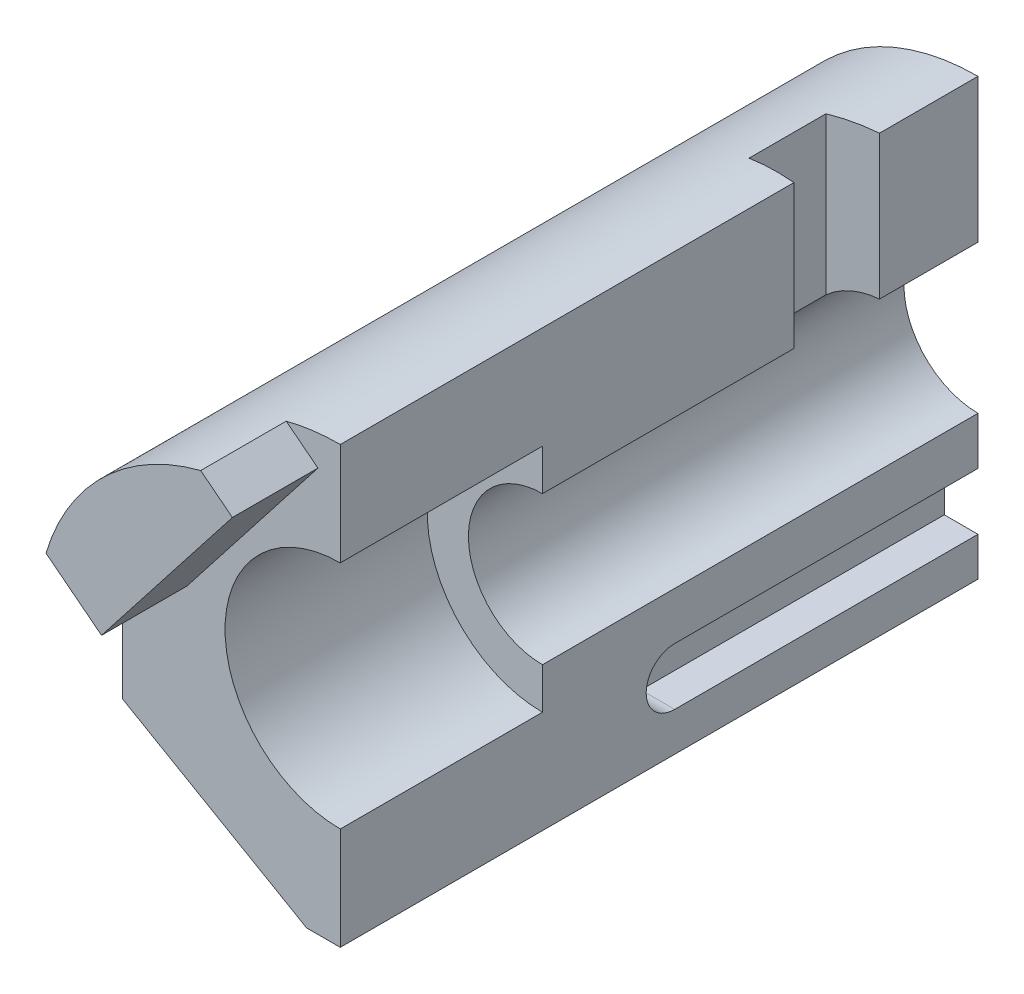
SolidWorks part; units mm, degrees
material "1060 Alloy"
ref_plane "Front Plane" through (0, 0, 0) normal (0, 0, 1) x (1, 0, 0)
ref_plane "Top Plane" through (0, 0, 0) normal (0, 1, 0) x (1, 0, 0)
ref_plane "Right Plane" through (0, 0, 0) normal (1, 0, 0) x (0, 0, -1)
sketch "Sketch2" plane through (0, 0, 0) normal (0, 0, 1) x (1, 0, 0)
  line L0 (0, 0) -> (0, 87075.3523) construction
  line L1 (0, 0) -> (87075.3523, 0) construction
  line L2 (0, -28.575) -> (0, -84)
  line L3 (0, -84) -> (-13, -84)
  line L4 (-13, -84) -> (-84, -43.0081)
  line L5 (-84, -43.0081) -> (-84, 0)
  line L6 (0, 84) -> (0, 28.575)
  line L7 (-13, -84) -> (-103.8778, -84) construction
  arc A0 (0, 28.575) -> (0, -28.575) centre (0, 0) ccw
  arc A1 (-84, 0) -> (0, 84) centre (0, 0) cw
  dimension "D4" = 84
  dimension "D5" = 28.575
  dimension "D1" = 84
  dimension "D2" = 84
  dimension "D3" = 13
  dimension "D6" = 30
extrude "Boss-Extrude1" add sketch "Sketch2" against normal blind 246
sketch "Sketch3" plane through (0, 0, 0) normal (0, 0, 1) x (1, 0, 0)
  line L0 (0, 0) -> (0, 50000) construction
  line L1 (0, 0) -> (50000, 0) construction
  line L2 (0, 44.45) -> (0, 28.575)
  line L3 (0, -28.575) -> (0, -44.45)
  arc A0 (0, 44.45) -> (0, -44.45) centre (0, 0) ccw
  arc A1 (0, 28.575) -> (0, -28.575) centre (0, 0) ccw construction
  arc A2 (0, 28.575) -> (0, -28.575) centre (0, 0) ccw
  dimension "D1" = 44.45
extrude "Cut-Extrude1" cut sketch "Sketch3" against normal blind 78 contours A0 L3 A2 L2
sketch "Sketch4" plane through (0, 0, 0) normal (0, 0, 1) x (1, 0, 0)
  line L0 (-20.8563, 81.3696) -> (-8.6176, 71.8077)
  line L1 (-8.6176, 71.8077) -> (-59.1018, 7.1908)
  line L2 (-59.1018, 7.1908) -> (-80.5207, 23.9251)
  line L3 (0, 0) -> (0, 50000) construction
  line L4 (0, 0) -> (50000, 0) construction
  line L5 (-30.0441, 36.5182) -> (-39430.5818, 30819.5919) construction
  line L6 (0, 0) -> (-30783.0738, -39400.5377) construction
  arc A0 (0, 84) -> (-84, 0) centre (0, 0) ccw construction
  arc A1 (-20.8563, 81.3696) -> (-80.5207, 23.9251) centre (0, 0) ccw
  point P12 (-33.8597, 39.4993)
  dimension "D1" = 82
  dimension "D2" = 38
  dimension "D3" = 38
  dimension "D4" = 38
  dimension "D5" = 41
  dimension "D6" = 82
  dimension "D7" = 51
extrude "Boss-Extrude2" add sketch "Sketch4" along normal blind 33
sketch "Sketch8" plane through (0, 0, 0) normal (1, 0, 0) x (0, 0, -1)
  line L0 (246, -47) -> (129, -47)
  line L1 (246, -84) -> (246, -28.575) construction
  line L2 (129, -69) -> (246, -69)
  line L3 (246, -47) -> (246, -69)
  line L4 (138.7463, -58) -> (50138.7463, -58) construction
  line L5 (246, -84) -> (0, -84) construction
  arc A0 (129, -47) -> (129, -69) centre (129, -58) ccw
  dimension "D2" = 11
  dimension "D1" = 26
  dimension "D3" = 117
extrude "Cut-Extrude4" cut sketch "Sketch8" against normal blind 13
ref_plane "Plane1" through (0, 90, 0) normal (0, 1, 0) x (1, 0, 0)
sketch "Sketch9" plane through (0, 90, 0) normal (0, 1, 0) x (1, 0, 0)
  line L0 (0, 0) -> (0, 50000) construction
  line L3 (0, 208) -> (-40.8003, 208) construction
  line L4 (0, 175) -> (-39.2064, 175) construction
  line L5 (0, 175) -> (0, 208)
  line L6 (0, 208) -> (-19, 206.3377)
  line L7 (-19, 206.3377) -> (-19, 176.6623)
  line L8 (-19, 176.6623) -> (0, 175)
  dimension "D1" = 38
  dimension "D2" = 33
  dimension "D3" = 19
  dimension "D4" = 5
  dimension "D5" = 5
extrude "Cut-Extrude5" cut sketch "Sketch9" against normal up to surface (61.425 mm away)
equation "\"A\" = 246.00"
equation "\"B\" = 117.00"
equation "\"C\" = 84.00"
equation "\"D1@Sketch2\"=\"C\""
equation "\"D2@Sketch2\"=\"C\""
equation "\"D4@Sketch2\"=\"C\""
equation "\"D1@Boss-Extrude1\"=\"A\""
equation "\"D3@Sketch8\"=\"B\""
equation "\"D\"= 5"
equation "\"D4@Sketch9\"=\"D\""
equation "\"D5@Sketch9\"=\"D\""
